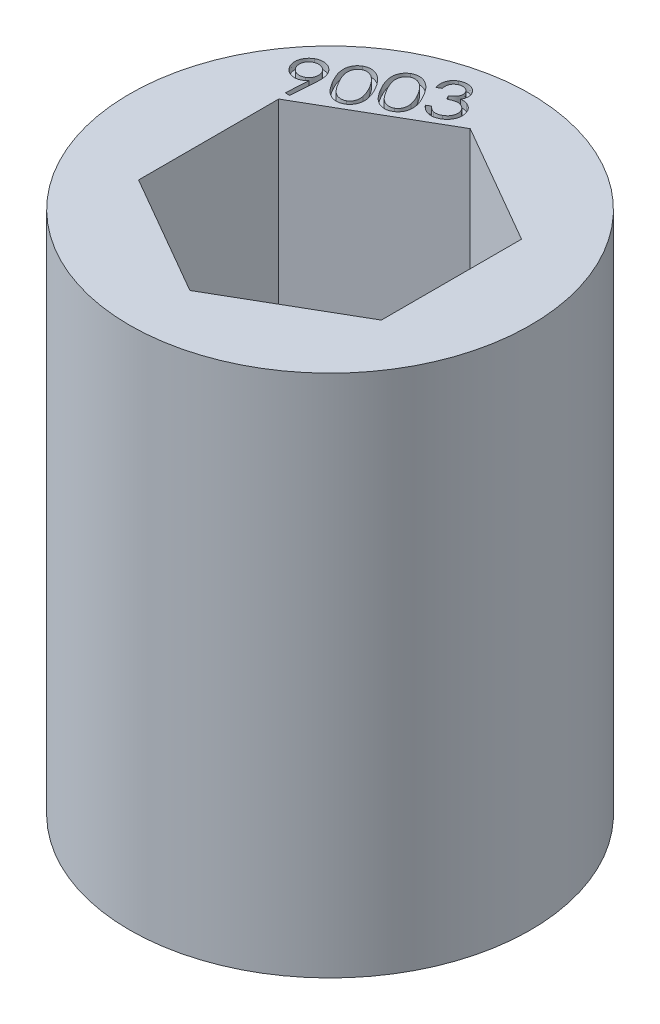
SolidWorks part; units mm, degrees
material "ABS"
ref_plane "Front Plane" through (0, 0, 0) normal (0, 0, 1) x (1, 0, 0)
ref_plane "Top Plane" through (0, 0, 0) normal (0, 1, 0) x (1, 0, 0)
ref_plane "Right Plane" through (0, 0, 0) normal (1, 0, 0) x (0, 0, -1)
sketch "Sketch1" plane through (0, 0, 0) normal (0, 1, 0) x (1, 0, 0)
  line L1 (6.731, 3.8861) -> (0, 7.7723)
  line L2 (0, 7.7723) -> (-6.731, 3.8861)
  line L3 (-6.731, 3.8861) -> (-6.731, -3.8861)
  line L4 (-6.731, -3.8861) -> (0, -7.7723)
  line L5 (0, -7.7723) -> (6.731, -3.8861)
  line L6 (6.731, -3.8861) -> (6.731, 3.8861)
  circle A0 centre (0, 0) radius 6.731 construction
  circle A1 centre (0, 0) radius 11.1125
  dimension "D1" = 22.225
  dimension "D2" = 13.462
extrude "Boss-Extrude1" add sketch "Sketch1" along normal blind 29.0449 contours A1 L6 L5 L4 L3 L2 L1
sketch "Sketch2" plane through (0, 29.0449, 0) normal (0, 1, 0) x (1, 0, 0)
  line L0 (-7.2176, 4.0745) -> (1.2613, 8.9698) construction
  line L1 (0, 7.7723) -> (-6.731, 3.8861) construction
  text T0 "9003" font "Century Gothic" height 2.54
  dimension "D1" = 0.4064
extrude "Cut-Extrude1" cut sketch "Sketch2" against normal blind 0.4
